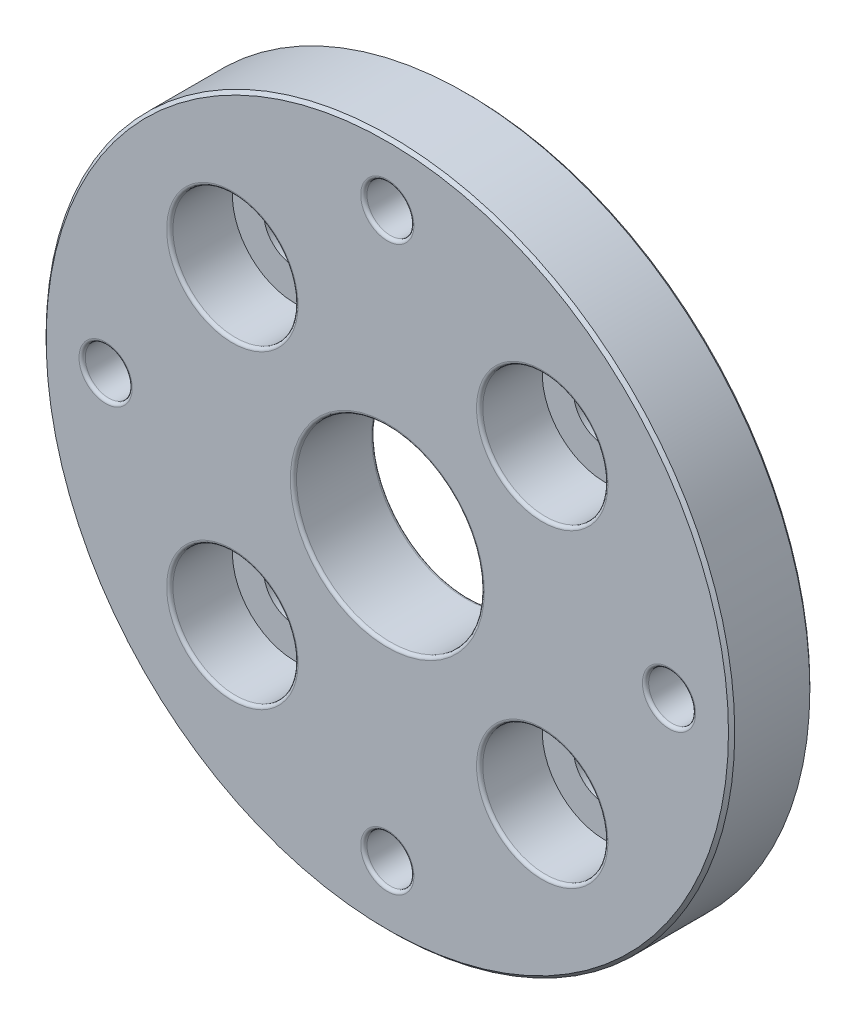
SolidWorks part; units mm, degrees
material "201 Annealed Stainless Steel (SS)"
ref_plane "Front Plane" through (0, 0, 0) normal (0, 0, 1) x (1, 0, 0)
ref_plane "Top Plane" through (0, 0, 0) normal (0, 1, 0) x (1, 0, 0)
ref_plane "Right Plane" through (0, 0, 0) normal (1, 0, 0) x (0, 0, -1)
sketch "Sketch1" plane through (0, 0, 0) normal (0, 0, 1) x (1, 0, 0)
  circle A0 centre (0, 0) radius 11
  dimension "D1" = 22
extrude "Boss-Extrude1" add sketch "Sketch1" along normal blind 2.6
sketch "Sketch2" plane through (0, 0, 2.6) normal (0, 0, 1) x (1, 0, 0)
  line L0 (0, 0) -> (4.9497, 4.9497) construction
  circle A0 centre (0, 0) radius 9 construction
  circle A1 centre (0, 0) radius 11 construction
  circle A2 centre (0, 9) radius 0.75
  circle A3 centre (9, 0) radius 0.75
  circle A4 centre (0, -9) radius 0.75
  circle A5 centre (-9, 0) radius 0.75
  circle A6 centre (0, 0) radius 7 construction
  circle A7 centre (4.9497, 4.9497) radius 1
  circle A8 centre (4.9497, -4.9497) radius 1
  circle A9 centre (-4.9497, -4.9497) radius 1
  circle A10 centre (-4.9497, 4.9497) radius 1
  point P16 (0, 0)
  point P26 (0, 0)
  dimension "D1" = 2
  dimension "D2" = 1.5
  dimension "D4" = 14
  dimension "D5" = 2
  dimension "D3" = 4
  dimension "D6" = 4
extrude "Cut-Extrude1" cut sketch "Sketch2" against normal through all
sketch "Sketch3" plane through (0, 0, 2.6) normal (0, 0, 1) x (1, 0, 0)
  circle A0 centre (4.9497, 4.9497) radius 2
  circle A1 centre (4.9497, -4.9497) radius 2
  circle A2 centre (-4.9497, -4.9497) radius 2
  circle A3 centre (-4.9497, 4.9497) radius 2
  point P12 (0, 0)
  dimension "D1" = 4
  dimension "D2" = 4
extrude "Cut-Extrude2" cut sketch "Sketch3" against normal blind 2
sketch "Sketch4" plane through (0, 0, 2.6) normal (0, 0, 1) x (1, 0, 0)
  circle A0 centre (0, 0) radius 3
  dimension "D1" = 6
extrude "Cut-Extrude3" cut sketch "Sketch4" against normal through all
chamfer "Chamfer1" distance 0.1 angle 45 2 edges at (11, 0, 0) (11, 0, 2.6)
fillet "Fillet1" radius 0.1 18 edges at (5.9497, 4.9497, 0) (9.75, 0, 0) (5.9497, -4.9497, 0) (0.75, -9, 0) (-3.9497, -4.9497, 0) (0.75, 9, 0) (-3.9497, 4.9497, 0) (-8.25, 0, 0) (9.75, 0, 2.6) (0.75, -9, 2.6) (-8.25, 0, 2.6) (0.75, 9, 2.6) (6.9497, -4.9497, 2.6) (-2.9497, -4.9497, 2.6) (-2.9497, 4.9497, 2.6) (3, 0, 2.6) (3, 0, 0) (6.9497, 4.9497, 2.6)
